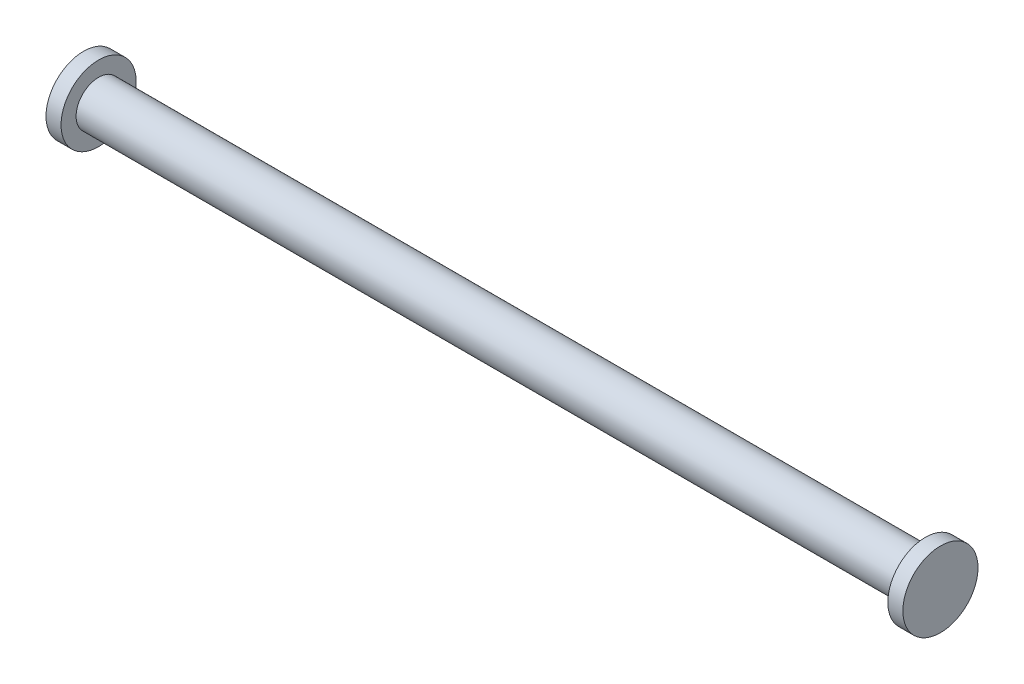
SolidWorks part; units mm, degrees
ref_plane "Front Plane" through (0, 0, 0) normal (0, 0, 1) x (1, 0, 0)
ref_plane "Top Plane" through (0, 0, 0) normal (0, 1, 0) x (1, 0, 0)
ref_plane "Right Plane" through (0, 0, 0) normal (1, 0, 0) x (0, 0, -1)
sketch "Sketch1" plane through (0, 0, 0) normal (1, 0, 0) x (0, 0, -1)
  circle A0 centre (0, 0) radius 3.81
  dimension "D1" = 7.62
extrude "Boss-Extrude1" add sketch "Sketch1" along normal blind 139.7
sketch "Sketch2" plane through (139.7, 0, 0) normal (1, 0, 0) x (0, 0, -1)
  circle A0 centre (0, 0) radius 6.35
  dimension "D1" = 12.7
extrude "Boss-Extrude2" add sketch "Sketch2" along normal blind 2.54 contours A0
sketch "Sketch3" plane through (0, 0, 0) normal (-1, 0, 0) x (0, 0, 1)
  circle A0 centre (0, 0) radius 6.35
extrude "Boss-Extrude3" add sketch "Sketch3" along normal blind 2.54 contours A0
